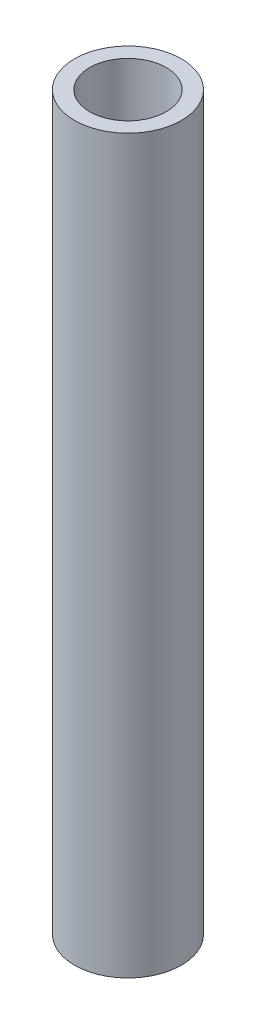
SolidWorks part; units mm, degrees
ref_plane "Front Plane" through (0, 0, 0) normal (0, 0, 1) x (1, 0, 0)
ref_plane "Top Plane" through (0, 0, 0) normal (0, 1, 0) x (1, 0, 0)
ref_plane "Right Plane" through (0, 0, 0) normal (1, 0, 0) x (0, 0, -1)
sketch "Sketch1" plane through (0, 0, 0) normal (0, 1, 0) x (1, 0, 0)
  circle A0 centre (0, 0) radius 7.6454
  circle A1 centre (0, 0) radius 10.668
  dimension "D1" = 21.336
  dimension "D2" = 15.2908
extrude "Boss-Extrude1" add sketch "Sketch1" along normal blind 146.05
ref_plane "Plane1" through (0, 73.025, 0) normal (0, 1, 0) x (1, 0, 0)
ref_plane "Plane2" through (0, 146.05, 0) normal (0, 1, 0) x (1, 0, 0)
